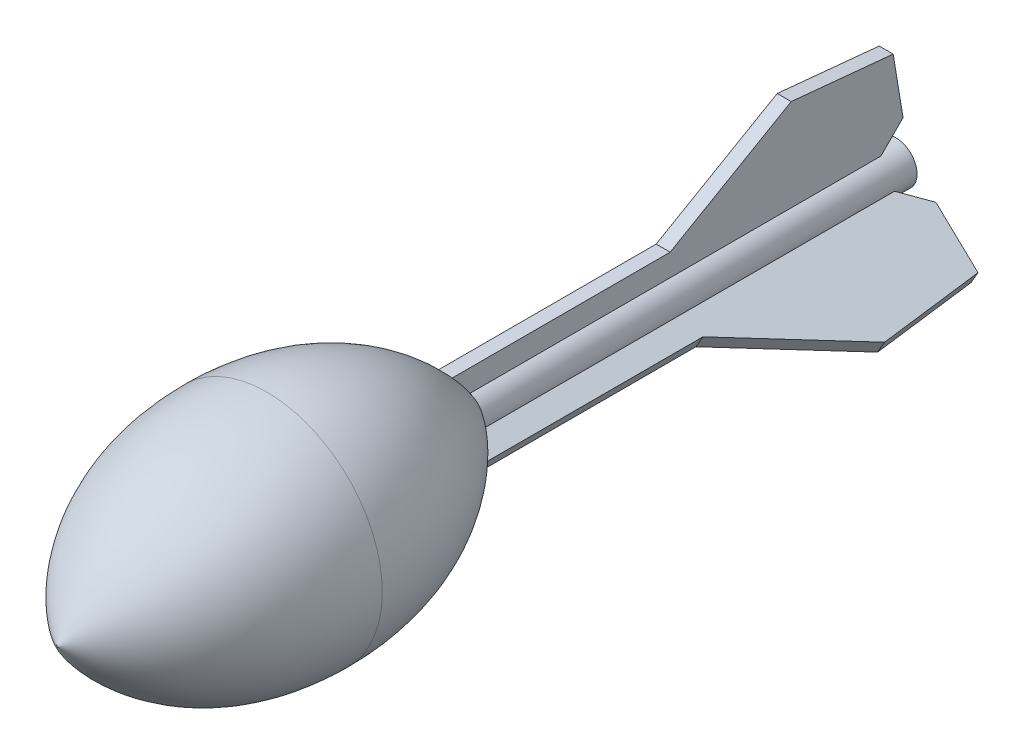
SolidWorks part; units mm, degrees
ref_plane "Front Plane" through (0, 0, 0) normal (0, 0, 1) x (1, 0, 0)
ref_plane "Top Plane" through (0, 0, 0) normal (0, 1, 0) x (1, 0, 0)
ref_plane "Right Plane" through (0, 0, 0) normal (1, 0, 0) x (0, 0, -1)
sketch "Sketch1" plane through (0, 0, 0) normal (1, 0, 0) x (0, 0, -1)
  line L0 (0, 0) -> (0, 41.275) construction
  line L1 (0, 0) -> (-75, 0) construction
  line L2 (0, 0) -> (75, 0) construction
  line L3 (-0.0549, 129.8088) -> (-149.9451, -129.8088) construction
  line L4 (45.6573, 41.275) -> (-45.6573, 41.275) construction
  line L5 (75, 0) -> (225, 0) construction
  line L6 (225, 0) -> (225, 7.5)
  line L7 (225, 7.5) -> (70.1206, 7.5)
  line L8 (-75, 0) -> (225, 0)
  spline S0 degree 3 poles (-75, 0) (-62.5, 21.6506) (-38.3333, 41.275) (0, 41.275) knots 0 0 0 0 1 1 1 1
  spline S1 degree 3 poles (70.1206, 7.5) (56.6412, 25.9807) (33.841, 41.275) (0, 41.275) knots 0.117191 0.117191 0.117191 0.117191 1 1 1 1
  dimension "D3" = 60
  dimension "D4" = 115
  dimension "D5" = 75
  dimension "D1" = 41.275
  dimension "D2" = 75
  dimension "D6" = 150
  dimension "D7" = 7.5
revolve "Revolve1" add sketch "Sketch1" angle 360 about L8
sketch "Sketch2" plane through (0, 0, 0) normal (1, 0, 0) x (0, 0, -1)
  line L0 (225, 15) -> (225, 40) construction
  line L1 (225, -7.5) -> (225, 7.5) construction
  line L2 (225, 40) -> (185, 40) construction
  line L3 (185, 40) -> (141.6987, 15)
  line L4 (141.6987, 15) -> (52.717, 15)
  line L5 (52.717, 15) -> (52.717, 0)
  line L6 (52.717, 0) -> (210, 0)
  line L7 (210, 0) -> (225, 15)
  line L8 (225, 40) -> (221.4645, 36.4645) construction
  line L9 (185, 40) -> (221.4645, 36.4645)
  line L10 (221.4645, 36.4645) -> (225, 15)
  point P0 (225, 0)
  dimension "D1" = 5
  dimension "D2" = 40
  dimension "D3" = 30
  dimension "D4" = 50
extrude "Boss-Extrude1" add sketch "Sketch2" along normal mid plane 5
pattern_circular "CirPattern2" count 3 over 360 about axis through (0, 0, 0) along (0, 0, 1) of "Boss-Extrude1"
sketch "Sketch4" plane through (0, 0, 0) normal (0, 0, 1) x (1, 0, 0)
  line L0 (-11.1125, -39.7509) -> (11.1125, -39.7509) construction
  line L1 (12.7467, -15.8917) -> (-34.9717, -63.6102) construction
  line L2 (26.8279, -55.4664) -> (-4.6029, -24.0355) construction
  line L3 (-11.1125, -39.7509) -> (-11.1125, -53.2525)
  line L4 (-11.1125, -53.2525) -> (11.1125, -53.2525)
  line L5 (11.1125, -53.2525) -> (11.1125, -40.0928)
  circle A0 centre (0, 0) radius 41.275 construction
  spline S0 degree 3 poles (-11.1125, -39.7509) (-3.1594, -31.7979) (5.874, -34.5125) (11.1125, -39.7509) knots 0 0 0 0 1 1 1 1
  dimension "D2" = 45
  dimension "D3" = 45
  dimension "D1" = 22.225
extrude "Cut-Extrude1" [suppressed] cut sketch "Sketch4" against normal through all both and the other way through all
pattern_circular "CirPattern3" [suppressed] count 3 over 360
